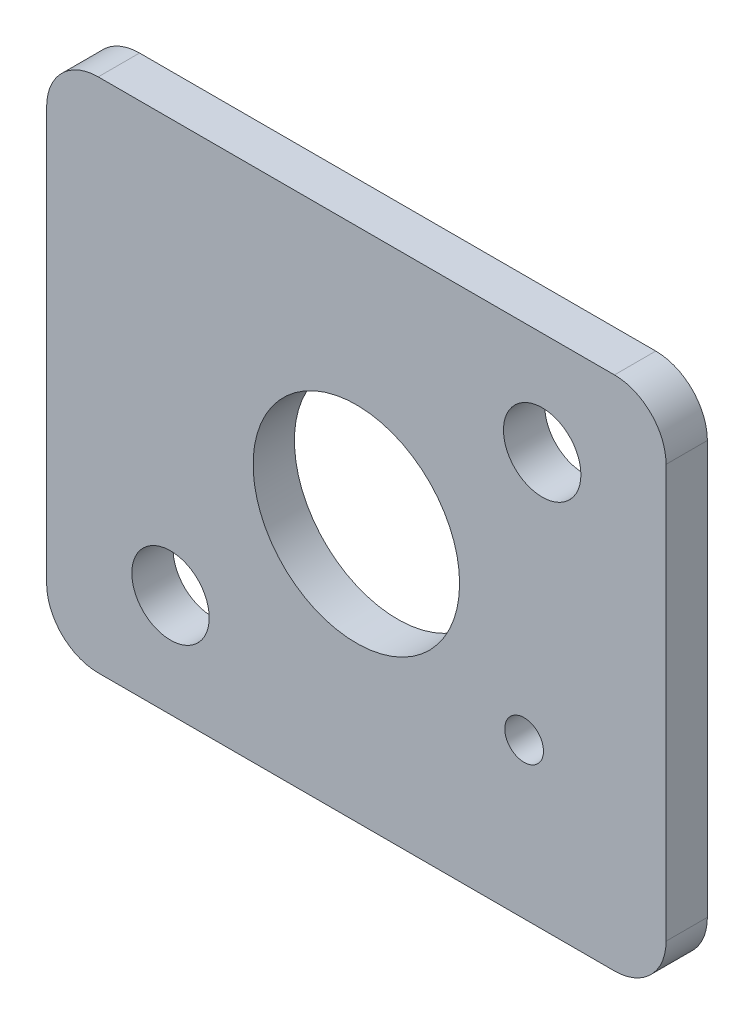
SolidWorks part; units mm, degrees
material "Латунь"
ref_plane "Спереди" through (0, 0, 0) normal (0, 0, 1) x (1, 0, 0)
ref_plane "Сверху" through (0, 0, 0) normal (0, 1, 0) x (1, 0, 0)
ref_plane "Справа" through (0, 0, 0) normal (1, 0, 0) x (0, 0, -1)
sketch "Эскиз1" plane through (0, 0, 0) normal (0, 0, 1) x (1, 0, 0)
  line L1 (-6, -5) -> (6, -5)
  line L2 (-6, -5) -> (-6, 5)
  line L3 (-6, 5) -> (6, 5)
  line L4 (6, -5) -> (6, 5)
  line L5 (-6, -5) -> (6, 5) construction
  line L6 (-6, 5) -> (6, -5) construction
  point P0 (0, 0)
  dimension "D1" = 12
  dimension "D2" = 10
extrude "Бобышка-Вытянуть1" add sketch "Эскиз1" along normal blind 0.8
sketch "Эскиз2" plane through (0, 0, 0.8) normal (0, 0, 1) x (1, 0, 0)
  line L0 (-6, -5) -> (6, 5) construction
  line L1 (-6, -5) -> (6, -5) construction
  line L4 (6, 5) -> (-6, 5) construction
  line L5 (6, -5) -> (6, 5) construction
  circle A0 centre (0, 0) radius 2
  circle A1 centre (-3.6, -3) radius 0.75
  circle A2 centre (3.6, 3) radius 0.75
  circle A3 centre (3.25, -2) radius 0.375
  dimension "D1" = 4
  dimension "D3" = 1.5
  dimension "D5" = 1.5
  dimension "D8" = 0.75
  dimension "D2" = 2
  dimension "D4" = 2
  dimension "D6" = 2.75
  dimension "D7" = 3
extrude "Вырез-Вытянуть1" cut sketch "Эскиз2" against normal up to next
fillet "Скругление1" radius 1 4 edges at (6, -5, 0.4) (-6, -5, 0.4) (-6, 5, 0.4) (6, 5, 0.4)
